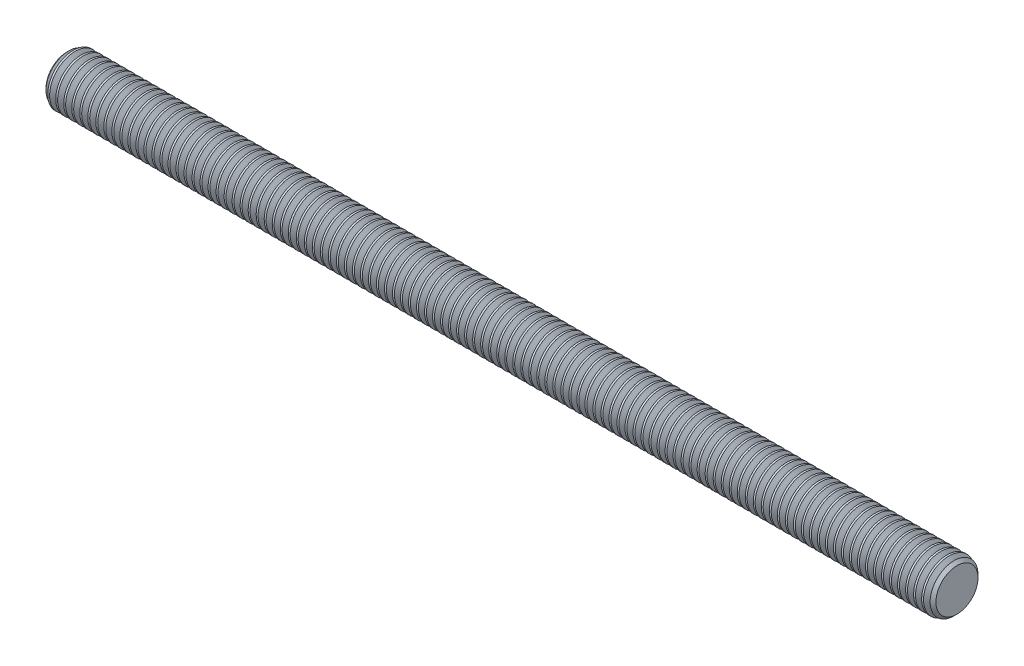
SolidWorks part; units mm, degrees
revolve "BaseBody" add sketch "BodySke" angle 360 about L14
sketch "BodySke" plane through (0, 0, 0) normal (0, 0, 1) x (1, 0, 0)
  line L0 (133.381, 15.875) -> (133.381, -6.35) construction
  line L1 (1.25, 15.875) -> (1.25, -3.175) construction
  line L2 (140, 6.35) -> (140, 3.175) construction
  line L10 (0, 4) -> (140, 4)
  line L12 (140, 4) -> (140, 0)
  line L13 (140, 0) -> (0, 0)
  line L14 (-3.175, 0) -> (107.95, 0) construction
  line L18 (0, 4) -> (0, 0)
  dimension "Diameter" = 8
  dimension "Length" = 140
  dimension "Advance" = 1.25
  dimension "Minor_dia" = 6.619
  dimension "Thread_max" = 140
cosmetic thread "ThreadCosmetic" [suppressed] parameters "Thread_minor"=6.619
ref_plane "Plane1" through (0, 0, 0) normal (0, 0, 1) x (1, 0, 0)
ref_plane "Plane2" through (0, 0, 0) normal (0, 1, 0) x (1, 0, 0)
ref_plane "Plane3" through (0, 0, 0) normal (1, 0, 0) x (0, 0, -1)
chamfer "Chamfer1" distance 0.6905 angle 45 2 edges at (0, 0, 4) (140, 0, 4)
sketch "ThdSchSke" plane through (0, 0, 0) normal (0, 0, 1) x (1, 0, 0)
  line L0 (0.4835, -3.3095) -> (0, -4)
  line L1 (0.4835, -3.3095) -> (0.967, -4)
  line L2 (0.967, -4) -> (0.967, -5)
  line L3 (-3.175, 0) -> (5.1513, 0) construction
  line L4 (0, 4) -> (0, -4) construction
  line L5 (0.967, -5) -> (0, -5)
  line L6 (0, -5) -> (0, -4)
  dimension "Thread_minor" = 6.619
  dimension "Diameter" = 8
revolve "ThreadSchematic" cut sketch "ThdSchSke" angle 360 about L3
pattern_linear "ThdSchPat" count 111 spacing 1.2613 along (1, 0, 0) of "ThreadSchematic"
equation "\"Thread_minor@ThreadCosmetic\" = \"Minor_dia@BodySke\""
equation "\"Chamfer@Chamfer1\" =  ( \"Diameter@BodySke\" - \"Minor_dia@BodySke\" ) / 2"
equation "\"Thread_minor@ThdSchSke\" = \"Minor_dia@BodySke\""
equation "\"Diameter@ThdSchSke\" = \"Diameter@BodySke\""
equation "\"Overcut@ThdSchSke\" = \"Diameter@BodySke\" * 1.25"
equation "\"Num_threads@ThdSchPat\" = int( (\"Thread_max@BodySke\" - \"Advance@BodySke\" ) / \"Advance@BodySke\" + 0.999 ) + 1"
equation "\"Advance@ThdSchPat\" = \"Thread_max@BodySke\" /  ( \"Num_threads@ThdSchPat\" - 1 ) 'relax it"
equation "\"Num_threads@ThdSchPat\" = \"Num_threads@ThdSchPat\" - sgn( \"Num_threads@ThdSchPat\" - 1 ) '---chamfered tips only---"
